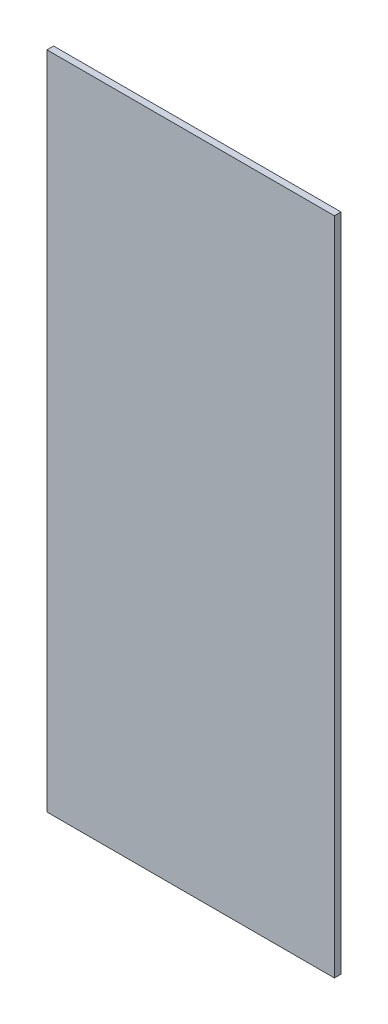
SolidWorks part; units mm, degrees
material "尼龙 6/10"
ref_plane "前视基准面" through (0, 0, 0) normal (0, 0, 1) x (1, 0, 0)
ref_plane "上视基准面" through (0, 0, 0) normal (0, 1, 0) x (1, 0, 0)
ref_plane "右视基准面" through (0, 0, 0) normal (1, 0, 0) x (0, 0, -1)
other "Configuration Table"
sketch "草图1" plane through (0, 0, 0) normal (0, 0, 1) x (1, 0, 0)
  line L1 (-2789.5, 3043.5438) -> (-2442.5, 3043.5438)
  line L2 (-2789.5, 3043.5438) -> (-2789.5, 2246.5438)
  line L3 (-2789.5, 2246.5438) -> (-2442.5, 2246.5438)
  line L4 (-2442.5, 3043.5438) -> (-2442.5, 2246.5438)
  dimension "D1" = 797
  dimension "D2" = 347
extrude "凸台-拉伸1" add sketch "草图1" along normal blind 8
